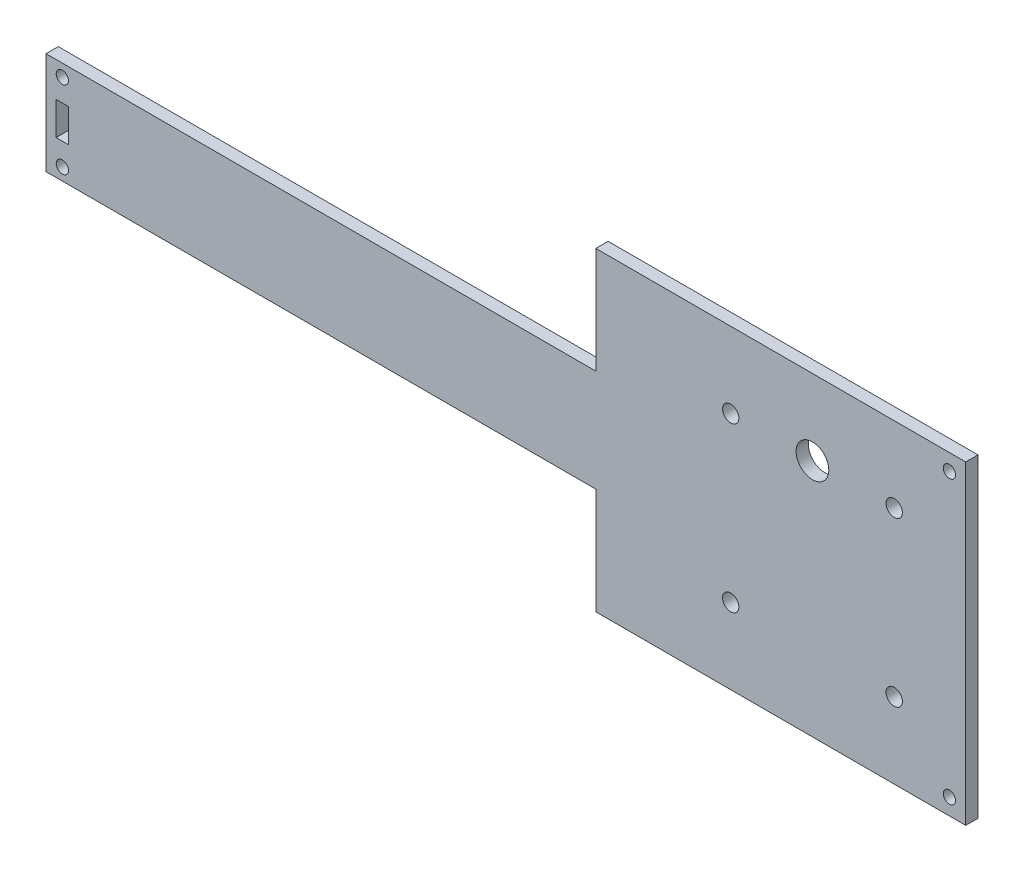
SolidWorks part; units mm, degrees
ref_plane "前视基准面" through (0, 0, 0) normal (0, 0, 1) x (1, 0, 0)
ref_plane "上视基准面" through (0, 0, 0) normal (0, 1, 0) x (1, 0, 0)
ref_plane "右视基准面" through (0, 0, 0) normal (1, 0, 0) x (0, 0, -1)
sketch "草图1" plane through (0, 0, 0) normal (0, 0, 1) x (1, 0, 0)
  line L1 (7.8468, 21.6171) -> (7.8468, -47.3829) construction
  line L3 (-209.1532, -22.3829) -> (-209.1532, -3.3829) construction
  line L5 (11.8468, 25.6171) -> (11.8468, -51.3829)
  line L7 (-213.1532, -25.3829) -> (-213.1532, -0.3829)
  line L8 (-25.6532, 21.6171) -> (-25.6532, -47.3829) construction
  line L9 (-25.6532, -12.8829) -> (-5.6532, -12.8829) construction
  line L10 (-5.6532, -12.8829) -> (-5.6532, -32.8829) construction
  line L11 (-45.6532, 7.1171) -> (-5.6532, 7.1171) construction
  line L12 (-63.1532, 25.6171) -> (11.8468, 25.6171) construction
  line L13 (11.8468, -51.3829) -> (-63.1532, -51.3829) construction
  line L14 (7.8468, -47.3829) -> (-59.1532, -47.3829) construction
  line L15 (-59.1532, 21.6171) -> (7.8468, 21.6171) construction
  line L16 (-59.1532, -47.3829) -> (-59.1532, 21.6171) construction
  line L17 (-63.1532, -51.3829) -> (-63.1532, 25.6171) construction
  line L20 (-209.1532, -12.8829) -> (-194.7823, -12.8829) construction
  line L21 (-213.1532, -12.8829) -> (-219.6725, -12.8829) construction
  line L22 (-210.7032, -8.8329) -> (-207.6032, -8.8329)
  line L23 (-210.7032, -8.8329) -> (-210.7032, -16.9329)
  line L24 (-210.7032, -16.9329) -> (-207.6032, -16.9329)
  line L25 (-207.6032, -8.8329) -> (-207.6032, -16.9329)
  line L26 (-210.7032, -8.8329) -> (-207.6032, -16.9329) construction
  line L27 (-210.7032, -16.9329) -> (-207.6032, -8.8329) construction
  line L28 (-213.1532, -0.3829) -> (-78.6473, -0.3829)
  line L29 (-78.6473, -0.3829) -> (-78.6473, 25.6171)
  line L30 (-78.6473, 25.6171) -> (11.8468, 25.6171)
  line L31 (-213.1532, -25.3829) -> (-78.6473, -25.3829)
  line L32 (-78.6473, -25.3829) -> (-78.6473, -51.3829)
  line L33 (-78.6473, -51.3829) -> (11.8468, -51.3829)
  circle A0 centre (-209.1532, -3.3829) radius 1.5
  circle A1 centre (7.8468, 21.6171) radius 1.5
  circle A2 centre (-209.1532, -22.3829) radius 1.5
  circle A3 centre (7.8468, -47.3829) radius 1.5
  circle A4 centre (-5.6532, -32.8829) radius 2
  circle A8 centre (-45.6532, -32.8829) radius 2
  circle A9 centre (-45.6532, 7.1171) radius 2
  circle A10 centre (-5.6532, 7.1171) radius 2
  circle A11 centre (-25.6532, 7.1171) radius 4
  dimension "D3" = 4
extrude "凸台-拉伸1" add sketch "草图1" along normal blind 3
